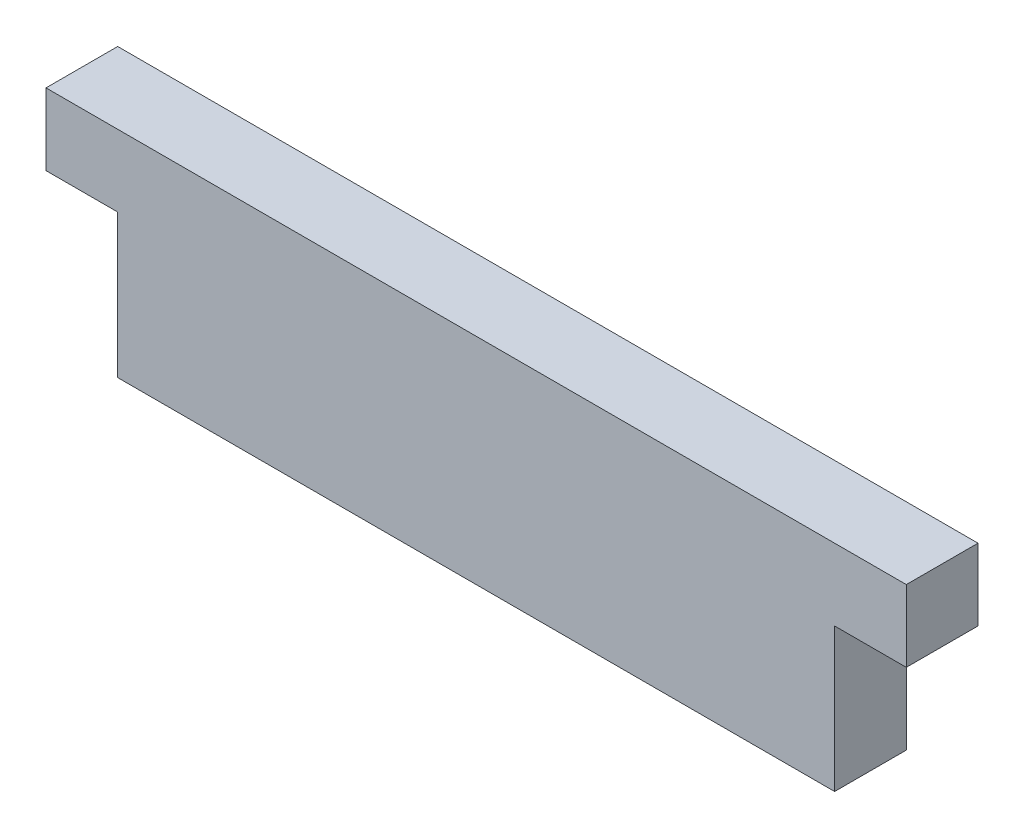
SolidWorks part; units mm, degrees
ref_plane "Front Plane" through (0, 0, 0) normal (0, 0, 1) x (1, 0, 0)
ref_plane "Top Plane" through (0, 0, 0) normal (0, 1, 0) x (1, 0, 0)
ref_plane "Right Plane" through (0, 0, 0) normal (1, 0, 0) x (0, 0, -1)
sketch "Sketch1" plane through (0, 0, 0) normal (0, 0, 1) x (1, 0, 0)
  line L1 (0, 0) -> (-50, 0)
  line L2 (0, 0) -> (0, -10)
  line L3 (0, -10) -> (-50, -10)
  line L4 (-50, 0) -> (-50, -10)
  line L5 (-55, 0) -> (5, 0)
  line L6 (-55, 0) -> (-55, 5)
  line L7 (-55, 5) -> (5, 5)
  line L8 (5, 0) -> (5, 5)
  dimension "D1" = 50
  dimension "D2" = 10
  dimension "D3" = 5
  dimension "D4" = 60
  dimension "D5" = 5
extrude "Boss-Extrude1" add sketch "Sketch1" along normal blind 5 contours L1 L4 L3 L2 | L5 L8 L7 L6 L1
